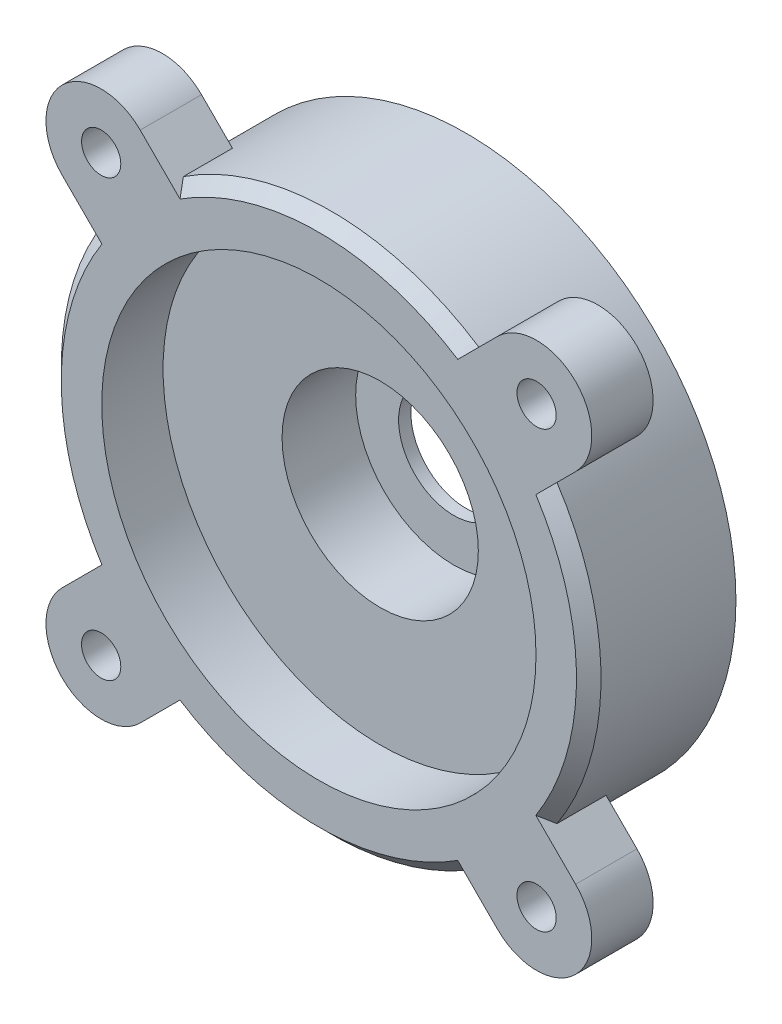
SolidWorks part; units mm, degrees
ref_plane "Front Plane" through (0, 0, 0) normal (0, 0, 1) x (1, 0, 0)
ref_plane "Top Plane" through (0, 0, 0) normal (0, 1, 0) x (1, 0, 0)
ref_plane "Right Plane" through (0, 0, 0) normal (1, 0, 0) x (0, 0, -1)
sketch "Sketch1" plane through (0, 0, 0) normal (0, 0, 1) x (1, 0, 0)
  circle A0 centre (0, 0) radius 22
  dimension "D1" = 44
extrude "Boss-Extrude1" add sketch "Sketch1" along normal mid plane 12
chamfer "Chamfer1" distance 1 angle 45 1 edges at (22, 0, 6)
sketch "Sketch8" plane through (0, 0, 6) normal (0, 0, 1) x (1, 0, 0)
  line L17 (20.9304, -14.5664) -> (17.6863, -11.3223)
  line L19 (14.5664, 20.9304) -> (11.3223, 17.6863)
  line L20 (20.9304, 14.5664) -> (17.6863, 11.3223)
  line L21 (17.6863, 11.3223) -> (11.3223, 17.6863)
  line L22 (14.5664, -20.9304) -> (11.3223, -17.6863)
  line L23 (11.3223, -17.6863) -> (17.6863, -11.3223)
  line L24 (-14.5664, -20.9304) -> (-11.3223, -17.6863)
  line L25 (-20.9304, -14.5664) -> (-17.6863, -11.3223)
  line L26 (-17.6863, -11.3223) -> (-11.3223, -17.6863)
  line L27 (-20.9304, 14.5664) -> (-17.6863, 11.3223)
  line L28 (-14.5664, 20.9304) -> (-11.3223, 17.6863)
  line L29 (-11.3223, 17.6863) -> (-17.6863, 11.3223)
  circle A2 centre (17.7484, 17.7484) radius 1.6
  circle A12 centre (0, 0) radius 21 construction
  arc A14 (14.5664, 20.9304) -> (20.9304, 14.5664) centre (17.7484, 17.7484) cw
  circle A15 centre (17.7484, -17.7484) radius 1.6
  arc A16 (20.9304, -14.5664) -> (14.5664, -20.9304) centre (17.7484, -17.7484) cw
  circle A17 centre (-17.7484, -17.7484) radius 1.6
  arc A18 (-14.5664, -20.9304) -> (-20.9304, -14.5664) centre (-17.7484, -17.7484) cw
  circle A19 centre (-17.7484, 17.7484) radius 1.6
  arc A20 (-20.9304, 14.5664) -> (-14.5664, 20.9304) centre (-17.7484, 17.7484) cw
  point P6 (17.7484, 17.7484)
  point P9 (0, 0)
  point P19 (17.7484, -17.7484)
  point P27 (-17.7484, -17.7484)
  point P31 (0, 0)
  point P36 (-17.7484, 17.7484)
  point P40 (0, 0)
  dimension "D1" = 4
extrude "Boss-Extrude2" add sketch "Sketch8" against normal blind 5
sketch "Sketch9" plane through (0, 0, 6) normal (0, 0, 1) x (1, 0, 0)
  circle A0 centre (0, 0) radius 17.7
extrude "Cut-Extrude1" cut sketch "Sketch9" against normal blind 5
sketch "Sketch10" plane through (0, 0, 1) normal (0, 0, 1) x (1, 0, 0)
  circle A0 centre (0, 0) radius 8
extrude "Cut-Extrude2" cut sketch "Sketch10" against normal blind 6
sketch "Sketch11" plane through (0, 0, -5) normal (0, 0, 1) x (1, 0, 0)
  circle A0 centre (0, 0) radius 4.5
extrude "Cut-Extrude3" cut sketch "Sketch11" against normal blind 1
